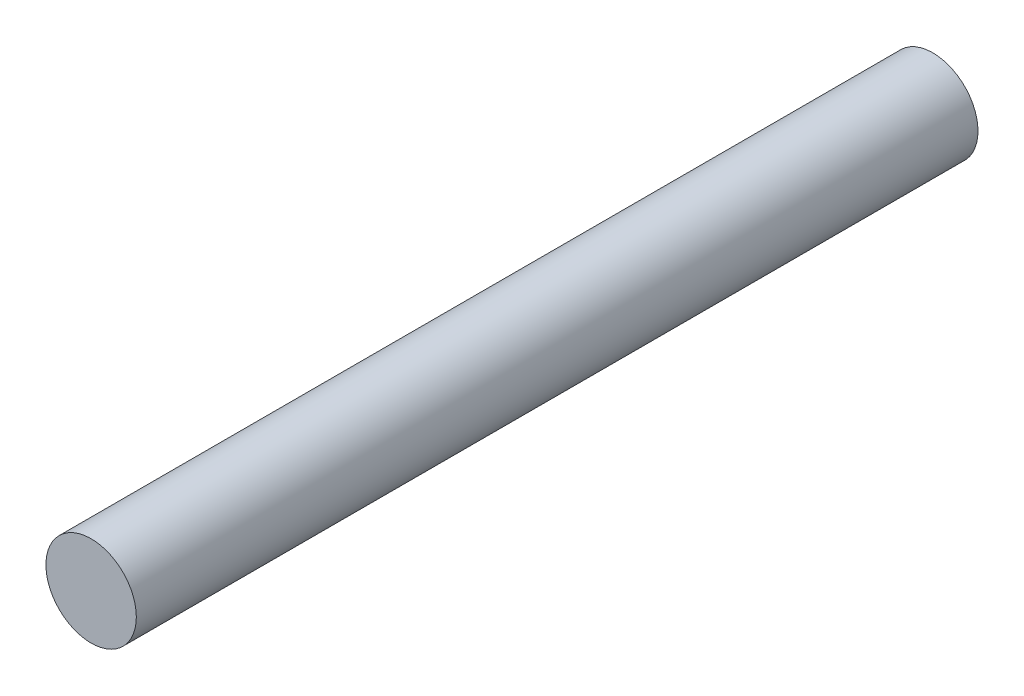
SolidWorks part; units mm, degrees
material "6061 Alloy"
ref_plane "Front Plane" through (0, 0, 0) normal (0, 0, 1) x (1, 0, 0)
ref_plane "Top Plane" through (0, 0, 0) normal (0, 1, 0) x (1, 0, 0)
ref_plane "Right Plane" through (0, 0, 0) normal (1, 0, 0) x (0, 0, -1)
sketch "Sketch1" plane through (0, 0, 0) normal (0, 0, 1) x (1, 0, 0)
  circle A0 centre (0, 0) radius 3
  dimension "D1" = 6
extrude "Boss-Extrude1" add sketch "Sketch1" along normal blind 55.855
